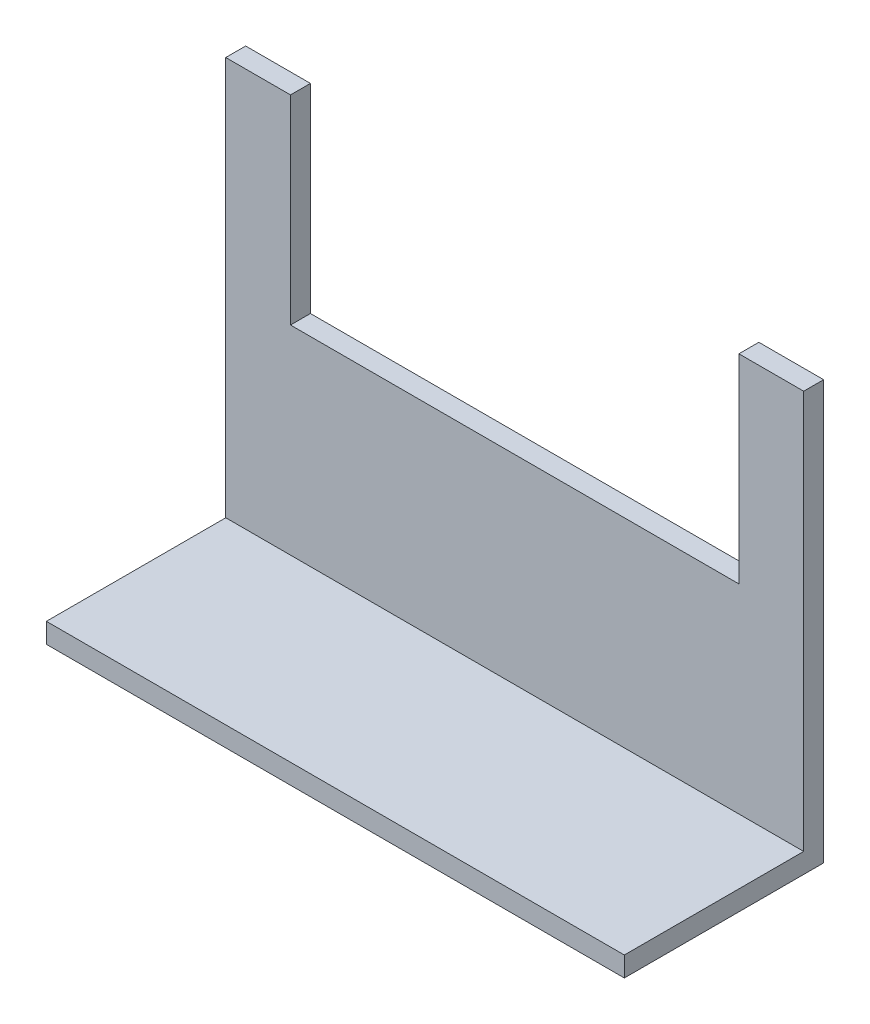
SolidWorks part; units mm, degrees
ref_plane "Front Plane" through (0, 0, 0) normal (0, 0, 1) x (1, 0, 0)
ref_plane "Top Plane" through (0, 0, 0) normal (0, 1, 0) x (1, 0, 0)
ref_plane "Right Plane" through (0, 0, 0) normal (1, 0, 0) x (0, 0, -1)
sketch "Sketch1" plane through (0, 0, 0) normal (0, 1, 0) x (1, 0, 0)
  line L1 (-29, 10) -> (29, 10)
  line L2 (-29, 10) -> (-29, -10)
  line L3 (-29, -10) -> (29, -10)
  line L4 (29, 10) -> (29, -10)
  line L5 (-29, 10) -> (29, -10) construction
  line L6 (-29, -10) -> (29, 10) construction
  point P0 (0, 0)
  dimension "D1" = 58
  dimension "D2" = 20
extrude "Boss-Extrude1" add sketch "Sketch1" along normal blind 2
sketch "Sketch2" plane through (0, 2, 0) normal (0, 1, 0) x (1, 0, 0)
  line L0 (29, -10) -> (29, 10) construction
  line L1 (-29, 10) -> (29, 10)
  line L2 (-29, 10) -> (-29, 8)
  line L3 (-29, 8) -> (29, 8)
  line L4 (29, 10) -> (29, 8)
  dimension "D1" = 2
extrude "Boss-Extrude2" add sketch "Sketch2" along normal blind 40
sketch "Sketch3" plane through (0, 0, -8) normal (0, 0, 1) x (1, 0, 0)
  line L0 (-29, 42) -> (29, 42)
  line L1 (-29, 42) -> (-29, 2) construction
  line L2 (-22.5, 61.7752) -> (22.5, 61.7752)
  line L3 (-22.5, 61.7752) -> (-22.5, 22)
  line L4 (-22.5, 22) -> (22.5, 22)
  line L5 (22.5, 61.7752) -> (22.5, 22)
  dimension "D1" = 6.5
  dimension "D2" = 20
extrude "Cut-Extrude1" cut sketch "Sketch3" against normal blind 60 contours L5 L0 L3 L4
